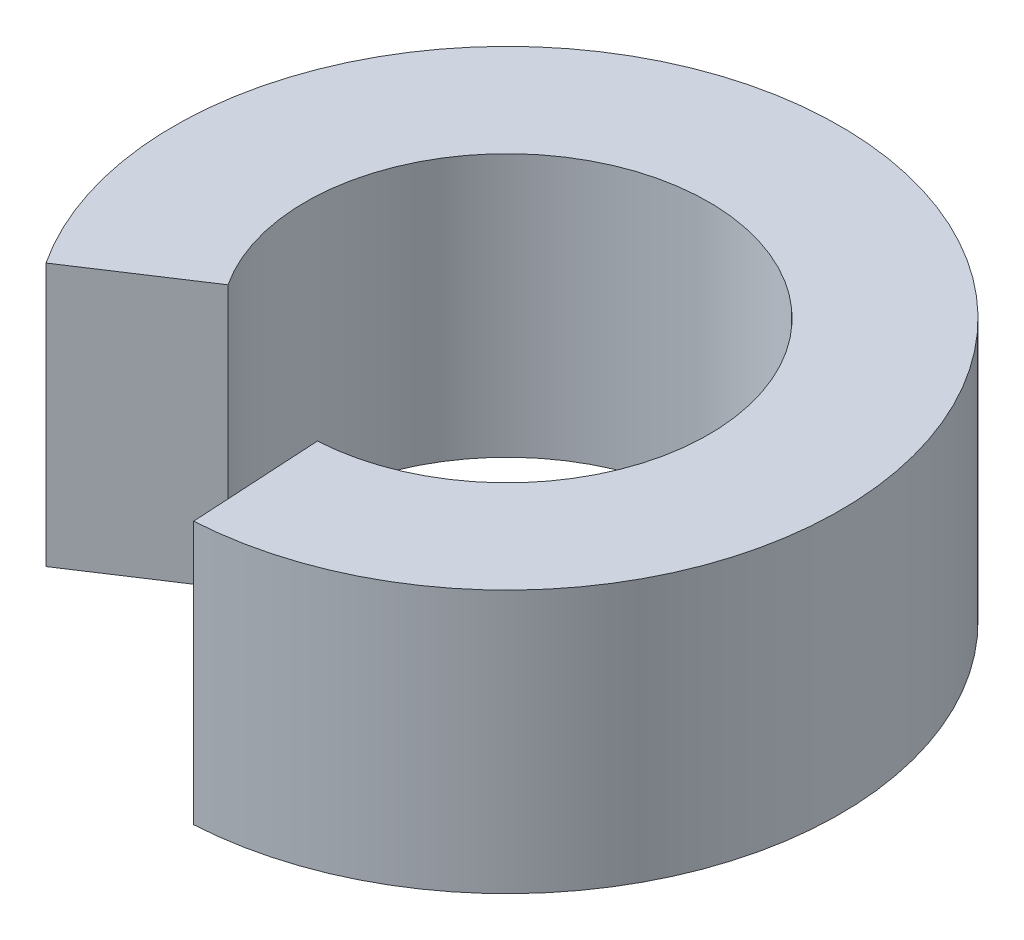
SolidWorks part; units mm, degrees
ref_plane "Front Plane" through (0, 0, 0) normal (0, 0, 1) x (1, 0, 0)
ref_plane "Top Plane" through (0, 0, 0) normal (0, 1, 0) x (1, 0, 0)
ref_plane "Right Plane" through (0, 0, 0) normal (1, 0, 0) x (0, 0, -1)
sketch "Sketch3" plane through (0, 0, 0) normal (0, 1, 0) x (1, 0, 0)
  line L0 (-1.9229, -1.2619) -> (-3.177, -2.0849)
  line L1 (0.1314, -2.2962) -> (0.2171, -3.7938)
  arc A0 (-1.9229, -1.2619) -> (0.1314, -2.2962) centre (0, 0) cw
  arc A1 (-3.177, -2.0849) -> (0.2171, -3.7938) centre (0, 0) cw
  dimension "D1" = 2.3
  dimension "D2" = 1.5
extrude "Boss-Extrude1" add sketch "Sketch3" along normal blind 3
